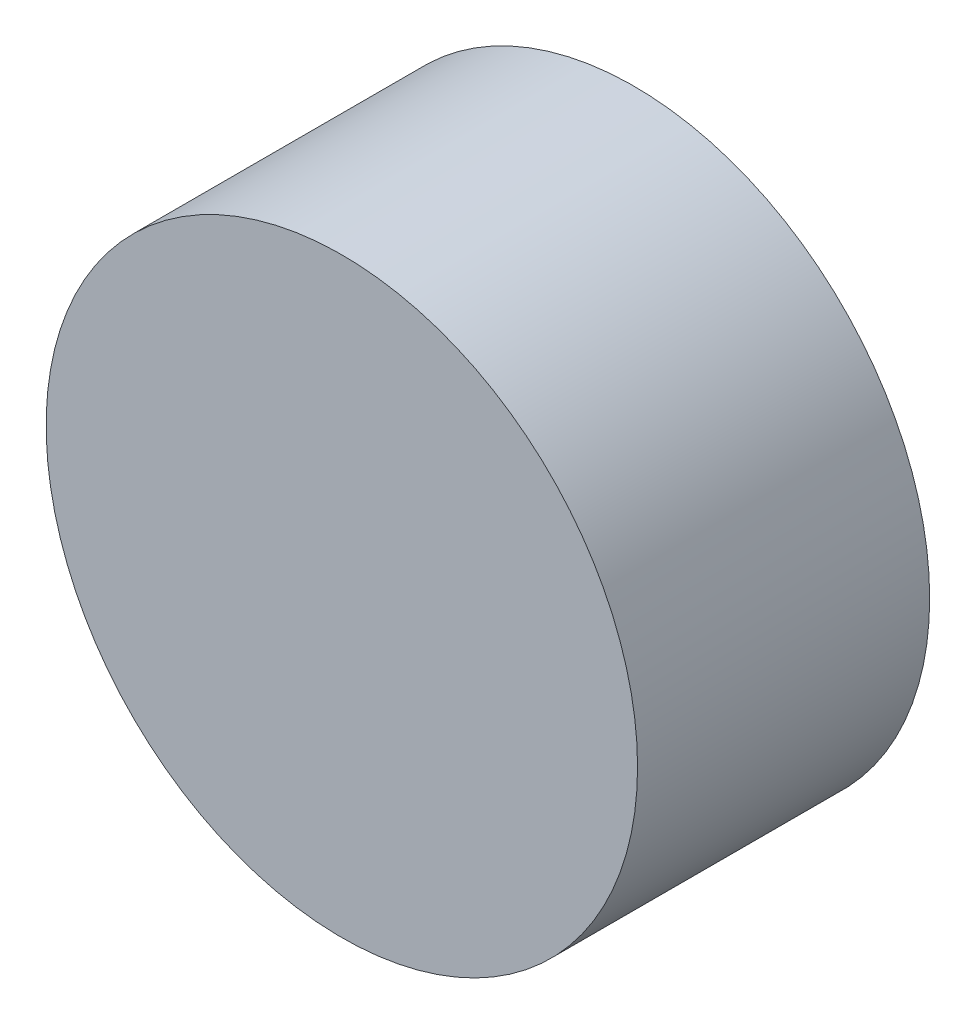
SolidWorks part; units mm, degrees
ref_plane "Front" through (0, 0, 0) normal (0, 0, 1) x (1, 0, 0)
ref_plane "Top" through (0, 0, 0) normal (0, 1, 0) x (1, 0, 0)
ref_plane "Right" through (0, 0, 0) normal (1, 0, 0) x (0, 0, -1)
sketch "Sketch1" plane through (0, 0, 0) normal (0, 0, 1) x (1, 0, 0)
  circle A0 centre (0, 0) radius 10.1235
extrude "Boss-Extrude1" add sketch "Sketch1" along normal blind 10
